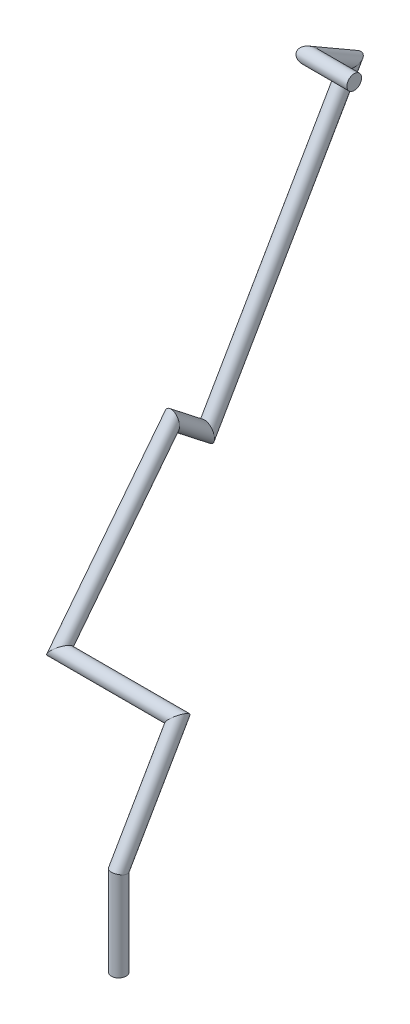
SolidWorks part; units mm, degrees
ref_plane "Front Plane" through (0, 0, 0) normal (0, 0, 1) x (1, 0, 0)
ref_plane "Top Plane" through (0, 0, 0) normal (0, 1, 0) x (1, 0, 0)
ref_plane "Right Plane" through (0, 0, 0) normal (1, 0, 0) x (0, 0, -1)
sketch3d "3DSketch1"
  line L0 (0, 0, 0) -> (0, 30, 0)
  line L1 (0, 30, 0) -> (0, 64.641, -20)
  line L2 (0, 64.641, -20) -> (-40, 64.641, -20)
  line L3 (0, 64.641, -20) -> (0, 128.8153, -70.1385) construction
  line L4 (-40, 64.641, -20) -> (-40, 113.4977, -58.171)
  line L5 (-40, 113.4977, -58.171) -> (-40, 104.2628, -69.9912)
  line L6 (-40, 104.2628, -69.9912) -> (-40, 189.1333, -118.9912)
  line L7 (-40, 113.4977, -58.171) -> (54.4925, 113.4977, -58.171) construction
  line L8 (-40, 189.1333, -118.9912) -> (-40, 197.1333, -105.1348)
  line L9 (-40, 197.1333, -105.1348) -> (-25, 197.1333, -105.1348)
  point P11 (20, 73.3013, -25)
  point P12 (-40.6113, 73.3013, -25)
  point P13 (-52.4607, 196.3374, -102.7468)
  point P15 (-22.8638, 196.3374, -102.7468)
  dimension "D1" = 30
  dimension "D2" = 150
  dimension "D3" = 40
  dimension "D4" = 40
  dimension "D12" = 15
  dimension "D5" = 172
  dimension "D6" = 62
  dimension "D7" = 15
  dimension "D8" = 98
  dimension "D9" = 16
  dimension "D10" = 90
  dimension "D11" = 90
sweep "Sweep1" add path "3DSketch1" circular profile diameter 5 parameters "D3"=5
